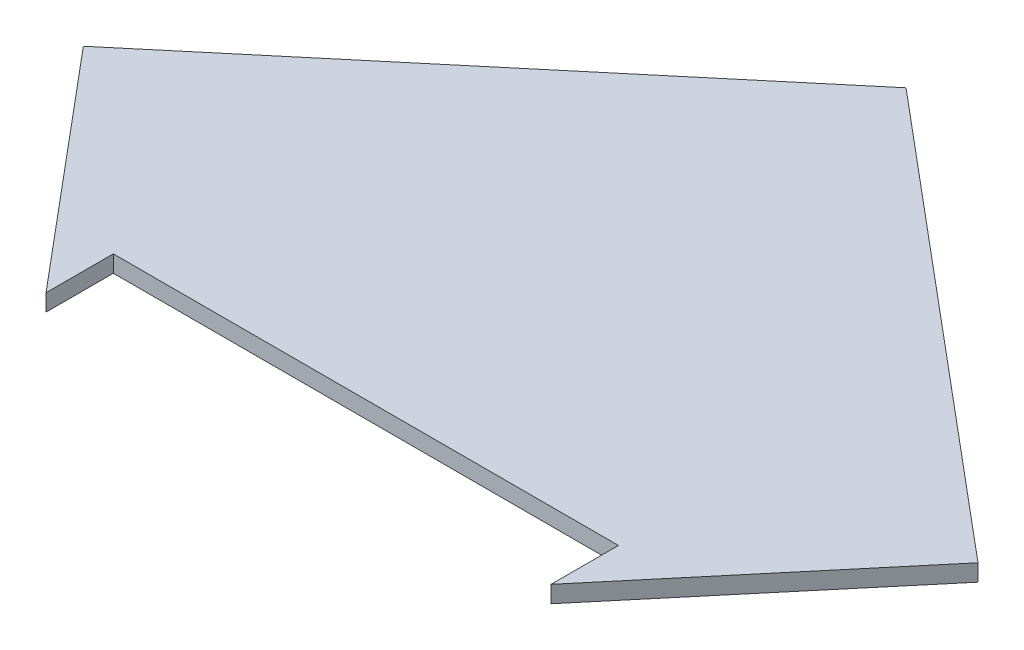
SolidWorks part; units mm, degrees
ref_plane "Front Plane" through (0, 0, 0) normal (0, 0, 1) x (1, 0, 0)
ref_plane "Top Plane" through (0, 0, 0) normal (0, 1, 0) x (1, 0, 0)
ref_plane "Right Plane" through (0, 0, 0) normal (1, 0, 0) x (0, 0, -1)
sketch "Sketch1" plane through (0, 0, 0) normal (0, 1, 0) x (1, 0, 0)
  line L0 (-95.25, 0) -> (95.25, 0)
  line L1 (-95.25, 0) -> (-95.25, -25.4)
  line L2 (95.25, 0) -> (95.25, -25.4)
  line L5 (-95.25, -25.4) -> (-168.7206, 62.1589)
  line L6 (95.25, -25.4) -> (168.7206, 62.1589)
  line L7 (0, 0) -> (0, 293.776) construction
  line L8 (-168.7206, 62.1589) -> (0, 203.7323)
  line L9 (0, 203.7323) -> (168.7206, 62.1589)
  point P3 (0, 0)
  point P7 (98.3729, -25.4)
  point P8 (0, 0)
  point P12 (-98.4667, -25.4)
  point P14 (-169.7775, 63.4184)
  dimension "D1" = 25.4
  dimension "D2" = 190.5
  dimension "D3" = 114.3
  dimension "D4" = 90
  dimension "D5" = 40
  dimension "D6" = 40
extrude "Boss-Extrude1" add sketch "Sketch1" along normal blind 6.35
